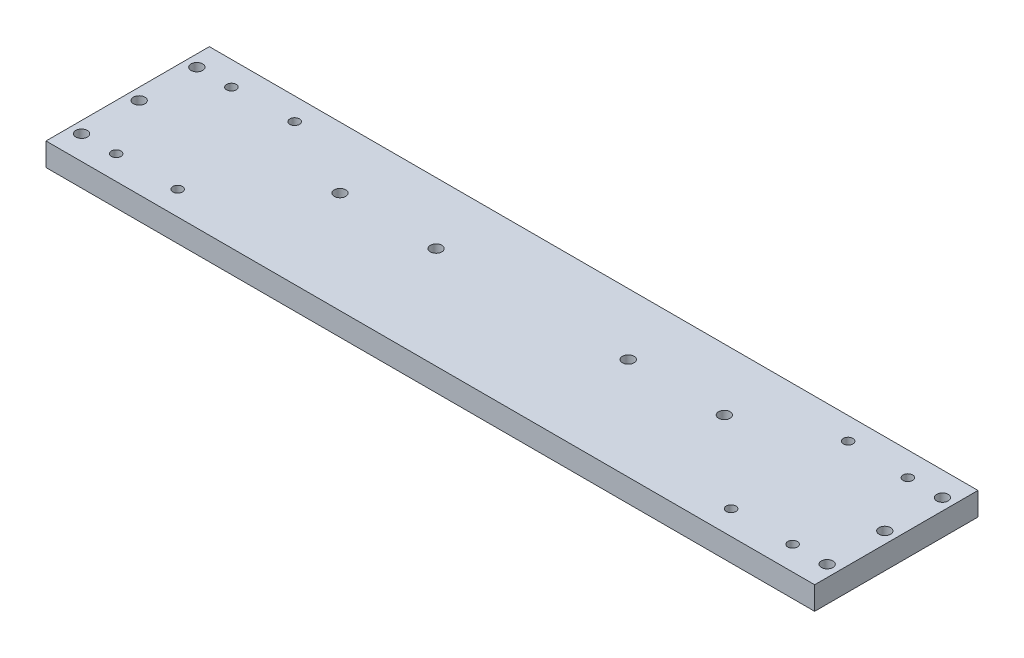
SolidWorks part; units mm, degrees
material "Beech"
ref_plane "Front Plane" through (0, 0, 0) normal (0, 0, 1) x (1, 0, 0)
ref_plane "Top Plane" through (0, 0, 0) normal (0, 1, 0) x (1, 0, 0)
ref_plane "Right Plane" through (0, 0, 0) normal (1, 0, 0) x (0, 0, -1)
sketch "Sketch1" plane through (0, 0, 0) normal (0, 1, 0) x (1, 0, 0)
  line L1 (-200, -42.5) -> (200, -42.5)
  line L2 (-200, -42.5) -> (-200, 42.5)
  line L3 (-200, 42.5) -> (200, 42.5)
  line L4 (200, -42.5) -> (200, 42.5)
  line L5 (-200, -42.5) -> (200, 42.5) construction
  line L6 (-200, 42.5) -> (200, -42.5) construction
  point P0 (0, 0)
  dimension "D1" = 400
  dimension "D2" = 85
extrude "Boss-Extrude1" add sketch "Sketch1" along normal blind 12
sketch "Sketch2" plane through (0, 12, 0) normal (0, 1, 0) x (1, 0, 0)
  line L0 (0, 59.82) -> (0, -66.3342) construction
  line L1 (-160, 59.82) -> (-160, -66.3342) construction
  line L2 (-176, 59.82) -> (-176, -66.3342) construction
  line L3 (-144, 59.82) -> (-144, -66.3342) construction
  line L4 (-186.7979, 0) -> (-131.8231, 0) construction
  line L5 (-186.7979, -30) -> (-131.8231, -30) construction
  line L6 (-186.7979, 30) -> (-131.8231, 30) construction
  line L7 (200, 42.5) -> (-200, 42.5) construction
  circle A0 centre (-176, -30) radius 2.5
  circle A1 centre (-144, -30) radius 2.5
  circle A2 centre (-144, 30.9185) radius 2.5
  circle A3 centre (-176, 30) radius 2.5
  dimension "D6" = 5
  dimension "D7" = 5
  dimension "D8" = 5
  dimension "D9" = 5
  dimension "D1" = 160
  dimension "D10" = 42.5
  dimension "D2" = 16
  dimension "D3" = 16
  dimension "D4" = 30
  dimension "D5" = 30
extrude "Cut-Extrude1" cut sketch "Sketch2" against normal up to next
mirror "Mirror1" about plane through (0, 0, 0) normal (1, 0, 0) of "Cut-Extrude1"
sketch "Sketch3" plane through (0, 12, 0) normal (0, 1, 0) x (1, 0, 0)
  line L0 (209.5508, 10.5) -> (-236.6399, 10.5) construction
  line L1 (200, 42.5) -> (-200, 42.5) construction
  line L2 (0, 47.0143) -> (0, -48.1051) construction
  circle A0 centre (50, 10.5) radius 3
  circle A1 centre (100, 10.5) radius 3
  circle A2 centre (-100, 10.5) radius 3
  circle A3 centre (-50, 10.5) radius 3
  dimension "D2" = 6
  dimension "D3" = 6
  dimension "D4" = 6
  dimension "D5" = 6
  dimension "D6" = 50
  dimension "D7" = 50
  dimension "D8" = 50
  dimension "D9" = 50
  dimension "D1" = 32
extrude "Cut-Extrude2" cut sketch "Sketch3" against normal up to next
sketch "Sketch4" plane through (0, 12, 0) normal (0, 1, 0) x (1, 0, 0)
  line L0 (-194, 51.4569) -> (-194, -59.6447) construction
  line L1 (-200, 42.5) -> (-200, -42.5) construction
  line L2 (-211.164, 0) -> (-178.8848, 0) construction
  circle A0 centre (-194, 0) radius 3
  circle A1 centre (-194, 30) radius 3
  circle A2 centre (-194, -30) radius 3
  dimension "D2" = 6
  dimension "D3" = 6
  dimension "D4" = 6
  dimension "D5" = 30
  dimension "D6" = 30
  dimension "D1" = 6
extrude "Cut-Extrude3" cut sketch "Sketch4" against normal up to next
mirror "Mirror2" about plane through (0, 0, 0) normal (1, 0, 0) of "Cut-Extrude3"
